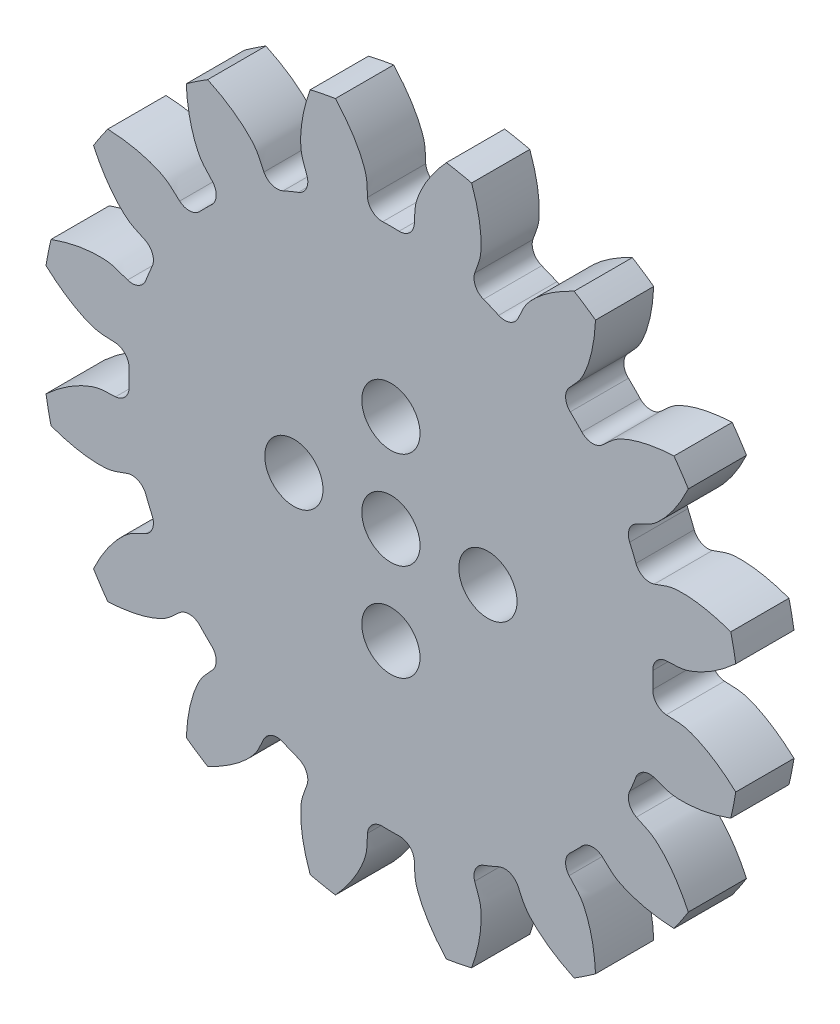
SolidWorks part; units mm, degrees
ref_plane "Front" through (0, 0, 0) normal (0, 0, 1) x (1, 0, 0)
ref_plane "Top" through (0, 0, 0) normal (0, 1, 0) x (1, 0, 0)
ref_plane "Right" through (0, 0, 0) normal (1, 0, 0) x (0, 0, -1)
ref_axis "Axis1" through (0, 0, -80.9) along (0, 0, 1)
sketch "草图1" plane through (0, 0, 0) normal (0, 0, 1) x (1, 0, 0)
  circle A0 centre (0, 0) radius 18
extrude "LaShenA" add sketch "草图1" along normal blind 3
sketch "SketchA" plane through (0, 0, 3) normal (0, 0, 1) x (1, 0, 0)
  line L0 (0, 0) -> (0, 18) construction
  arc A0 (0.4232, 13.4934) -> (-0.4232, 13.4934) centre (0, 0) ccw
  arc A1 (3.858, 18.7275) -> (-3.858, 18.7275) centre (0, 0) ccw
  arc A2 (-0.4232, 13.4934) -> (-1.2044, 14.1898) centre (-0.447, 14.253) cw
  arc A3 (1.2044, 14.1898) -> (0.4232, 13.4934) centre (0.447, 14.253) cw
  circle A4 centre (0, 0) radius 15.0351 construction
  circle A5 centre (0, 0) radius 18 construction
  circle A6 centre (0, 0) radius 13.5 construction
  circle A7 centre (0, 0) radius 16 construction
  spline S0 degree 3 poles (1.2044, 14.1898) (1.2266, 14.4552) (1.2138, 14.7739) (1.2737, 15.1106) (1.2991, 15.2114) (1.3214, 15.2911) (1.3499, 15.3823) (1.3851, 15.4846) (1.4278, 15.5978) (1.4786, 15.7214) (1.5382, 15.8552) (1.6071, 15.9987) (1.686, 16.1514) (1.7754, 16.3129) (1.876, 16.4827) (1.9884, 16.6603) (2.1129, 16.8451) (2.2502, 17.0365) (2.4007, 17.234) (2.5649, 17.4369) (2.7432, 17.6446) (2.9361, 17.8564) (3.1439, 18.0718) (3.4474, 18.3685) (3.6895, 18.585) (3.858, 18.7275) knots 0.122308 0.122308 0.122308 0.122308 0.250611 0.276296 0.287604 0.300968 0.316388 0.333864 0.353395 0.374983 0.398627 0.424327 0.452082 0.481894 0.513762 0.547685 0.583665 0.6217 0.661792 0.703939 0.748143 0.794402 0.842718 0.893089 1 1 1 1
  spline S1 degree 3 poles (-1.2044, 14.1898) (-1.2266, 14.4552) (-1.2138, 14.7739) (-1.2737, 15.1106) (-1.2991, 15.2114) (-1.3214, 15.2911) (-1.3499, 15.3823) (-1.3851, 15.4846) (-1.4278, 15.5978) (-1.4786, 15.7214) (-1.5382, 15.8552) (-1.6071, 15.9987) (-1.686, 16.1514) (-1.7754, 16.3129) (-1.876, 16.4827) (-1.9884, 16.6603) (-2.1129, 16.8451) (-2.2502, 17.0365) (-2.4007, 17.234) (-2.5649, 17.4369) (-2.7432, 17.6446) (-2.9361, 17.8564) (-3.1439, 18.0718) (-3.4474, 18.3685) (-3.6895, 18.585) (-3.858, 18.7275) knots 0.122308 0.122308 0.122308 0.122308 0.250611 0.276296 0.287604 0.300968 0.316388 0.333864 0.353395 0.374983 0.398627 0.424327 0.452082 0.481894 0.513762 0.547685 0.583665 0.6217 0.661792 0.703939 0.748143 0.794402 0.842718 0.893089 1 1 1 1
  dimension "D1" = 0.76
  dimension "Db" = 30.0702
  dimension "Da" = 36
  dimension "Df" = 27
  dimension "Dn" = 32
extrude "Cut-ExtrudeA" cut sketch "SketchA" against normal blind 3
pattern_circular "www.KYTool.cn" count 16 over 360 about axis through (0, 0, -80.9) along (0, 0, 1) of "Cut-ExtrudeA"
sketch "草图3" plane through (0, 0, 0) normal (0, 0, -1) x (-1, 0, 0)
  circle A0 centre (0, 0) radius 1.5
extrude "切除-拉伸2" cut sketch "草图3" against normal blind 10
sketch "草图4" plane through (0, 0, 0) normal (0, 0, -1) x (-1, 0, 0)
  line L0 (0, 0) -> (5, 0)
  circle A0 centre (5, 0) radius 1.5
  circle A1 centre (0, -5) radius 1.5
  circle A2 centre (-5, 0) radius 1.5
  circle A3 centre (0, 5) radius 1.5
  point P13 (0, 0)
  dimension "D1" = 4
extrude "切除-拉伸3" cut sketch "草图4" against normal blind 10
